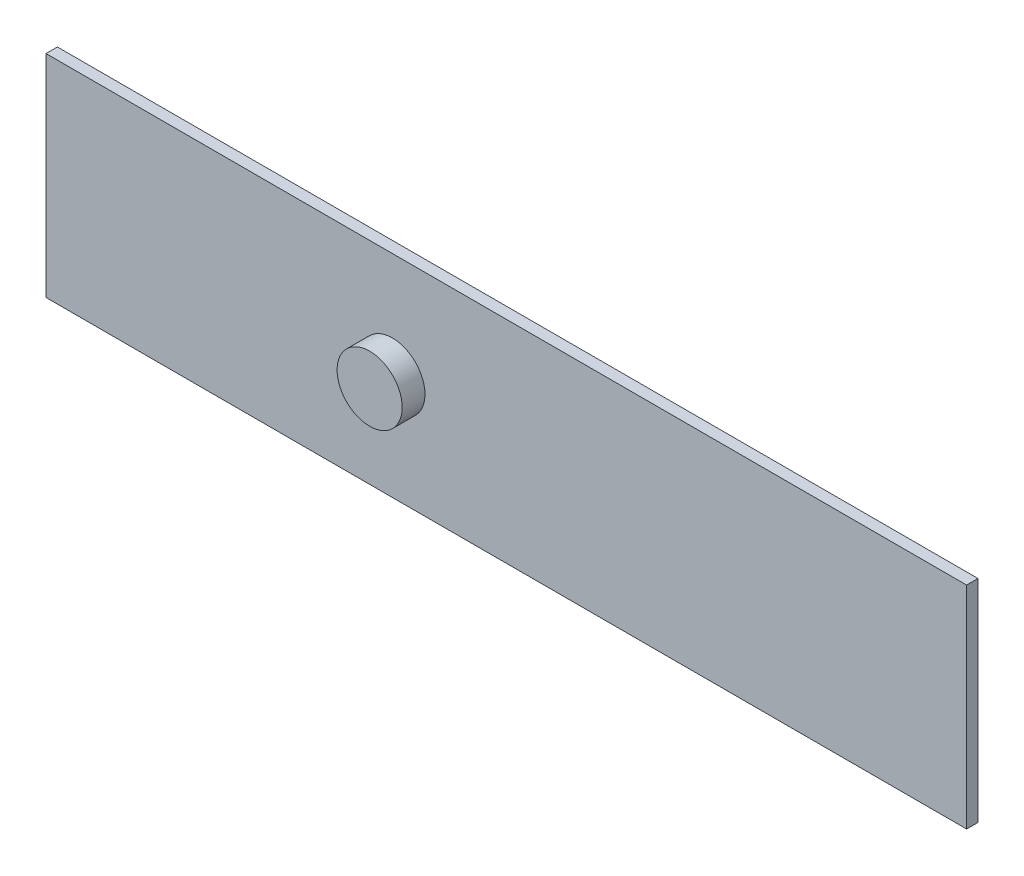
SolidWorks part; units mm, degrees
ref_plane "Front Plane" through (0, 0, 0) normal (0, 0, 1) x (1, 0, 0)
ref_plane "Top Plane" through (0, 0, 0) normal (0, 1, 0) x (1, 0, 0)
ref_plane "Right Plane" through (0, 0, 0) normal (1, 0, 0) x (0, 0, -1)
sketch "Sketch1" plane through (0, 0, 0) normal (0, 0, 1) x (1, 0, 0)
  line L0 (-282.94, -64.94) -> (-282.94, 64.94)
  line L1 (-282.94, -64.94) -> (282.94, -64.94)
  line L2 (-282.94, 64.94) -> (282.94, 64.94)
  line L3 (282.94, -64.94) -> (282.94, 64.94)
  line L4 (-282.94, -64.94) -> (282.94, 64.94) construction
  line L5 (-282.94, 64.94) -> (282.94, -64.94) construction
  point P1 (0, 0)
  dimension "D1" = 565.88
  dimension "D2" = 129.88
extrude "Boss-Extrude1" add sketch "Sketch1" along normal mid plane 7
sketch "Sketch2" plane through (0, 0, 3.5) normal (0, 0, 1) x (1, 0, 0)
  line L0 (-75.6823, 64.94) -> (75.6823, 64.94) construction
  line L1 (282.94, 64.94) -> (-282.94, 64.94) construction
  circle A0 centre (-70, 0) radius 20
  point P5 (0, 64.94)
  dimension "D1" = 40
  dimension "D2" = 70
  dimension "D3" = 64.94
extrude "Boss-Extrude2" add sketch "Sketch2" along normal blind 14
